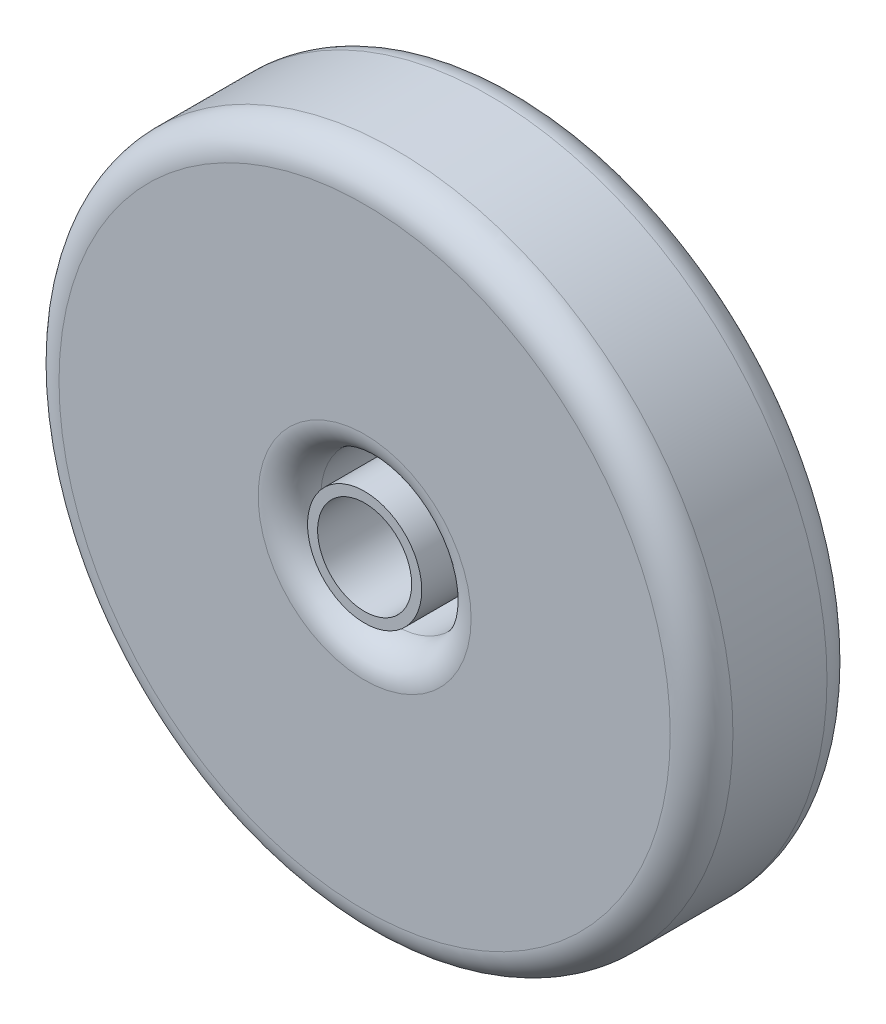
SolidWorks part; units mm, degrees
material "Nylon 101"
ref_plane "Front Plane" through (0, 0, 0) normal (0, 0, 1) x (1, 0, 0)
ref_plane "Top Plane" through (0, 0, 0) normal (0, 1, 0) x (1, 0, 0)
ref_plane "Right Plane" through (0, 0, 0) normal (1, 0, 0) x (0, 0, -1)
sketch "Sketch1" plane through (0, 0, 0) normal (0, 0, 1) x (1, 0, 0)
  circle A0 centre (0, 0) radius 27.305
  circle A1 centre (0, 0) radius 3.81
  dimension "D1" = 7.62
  dimension "D2" = 54.61
extrude "Boss-Extrude1" add sketch "Sketch1" along normal blind 12.7
sketch "Sketch2" plane through (0, 0, 12.7) normal (0, 0, 1) x (1, 0, 0)
  circle A0 centre (0, 0) radius 4.6264
  circle A1 centre (0, 0) radius 6.0892
  circle A2 centre (0, 0) radius 27.305 construction
  dimension "D1" = 9.2528
  dimension "D2" = 12.1784
extrude "Cut-Extrude1" cut sketch "Sketch2" against normal blind 10.16
fillet "Fillet2" radius 2.54 2 edges at (6.0892, 0, 12.7) (27.305, 0, 12.7)
fillet "Fillet3" radius 2.54 1 edges at (27.305, 0, 0)
